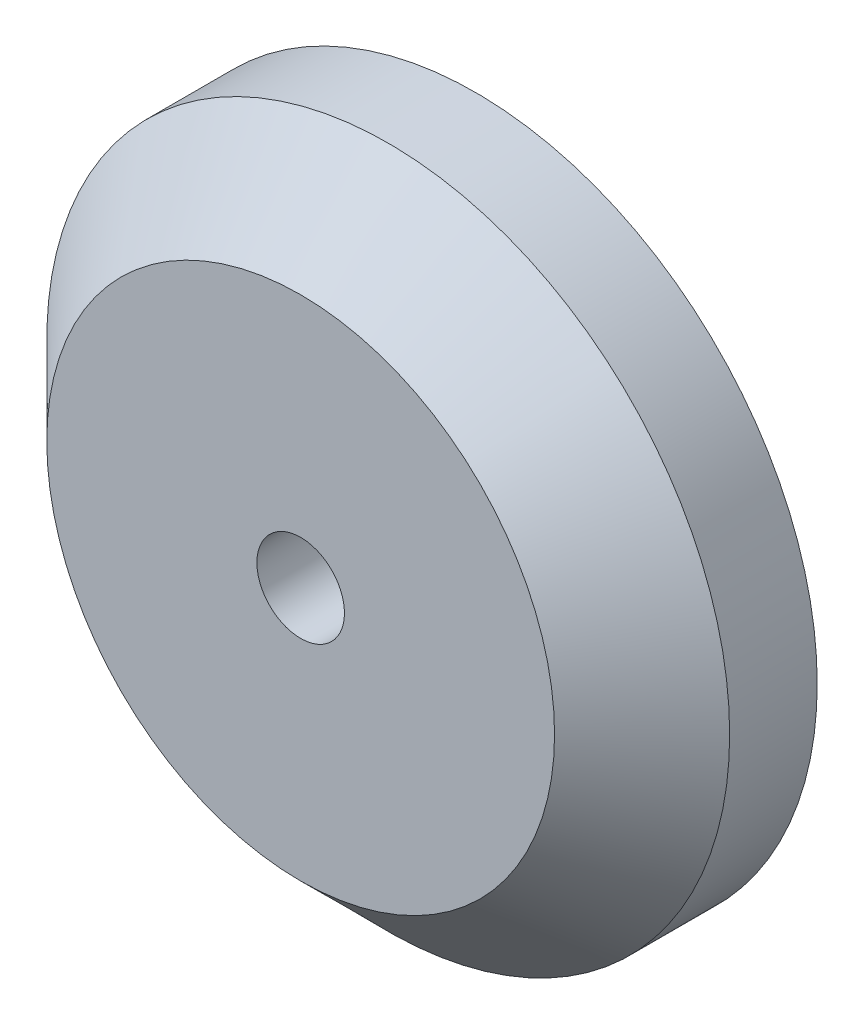
SolidWorks part; units mm, degrees
ref_plane "Front Plane" through (0, 0, 0) normal (0, 0, 1) x (1, 0, 0)
ref_plane "Top Plane" through (0, 0, 0) normal (0, 1, 0) x (1, 0, 0)
ref_plane "Right Plane" through (0, 0, 0) normal (1, 0, 0) x (0, 0, -1)
sketch "Sketch1" plane through (0, 0, 0) normal (0, 0, 1) x (1, 0, 0)
  circle A0 centre (0, 0) radius 9.75
  dimension "D1" = 19.5
extrude "Boss-Extrude1" add sketch "Sketch1" along normal blind 5
sketch "Sketch2" plane through (0, 0, 0) normal (0, 0, -1) x (-1, 0, 0)
  circle A0 centre (0, 0) radius 1.25
  dimension "D1" = 2.5
extrude "Cut-Extrude1" cut sketch "Sketch2" against normal blind 5
chamfer "Chamfer1" distance 2.5 angle 45 1 edges at (9.75, 0, 5)
sketch "Sketch4" plane through (0, 0, 0) normal (0, 0, -1) x (-1, 0, 0)
  circle A0 centre (0, 0) radius 2.5
  dimension "D1" = 5
extrude "Cut-Extrude3" cut sketch "Sketch4" against normal blind 2.5
